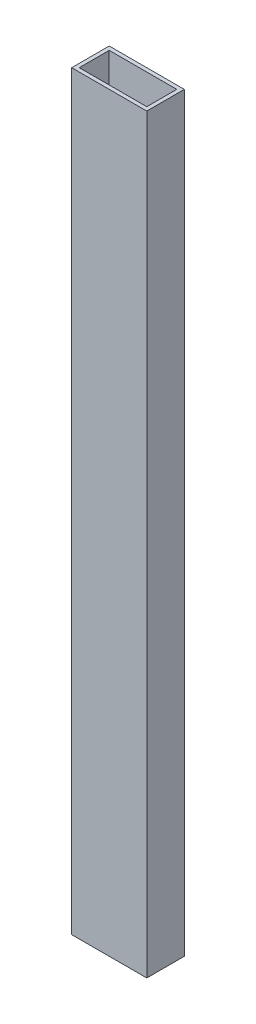
SolidWorks part; units mm, degrees
ref_plane "Plano frontal" through (0, 0, 0) normal (0, 0, 1) x (1, 0, 0)
ref_plane "Plano superior" through (0, 0, 0) normal (0, 1, 0) x (1, 0, 0)
ref_plane "Plano direito" through (0, 0, 0) normal (1, 0, 0) x (0, 0, -1)
sketch "Esboço1" plane through (0, 0, 0) normal (0, 1, 0) x (1, 0, 0)
  line L0 (-18, -8) -> (-18, 8)
  line L1 (-20, -10) -> (20, -10)
  line L2 (-20, -10) -> (-20, 10)
  line L3 (-20, 10) -> (20, 10)
  line L4 (20, -10) -> (20, 10)
  line L5 (-20, -10) -> (20, 10) construction
  line L6 (-20, 10) -> (20, -10) construction
  line L7 (-18, 8) -> (18, 8)
  line L8 (18, -8) -> (18, 8)
  line L9 (-18, -8) -> (18, -8)
  point P0 (0, 0)
  dimension "D1" = 40
  dimension "D2" = 20
  dimension "D3" = 2
sketch "Esboço2" plane through (0, 0, 0) normal (1, 0, 0) x (0, 0, -1)
  line L0 (0, 0) -> (0, -400)
  dimension "D1" = 400
sweep "Varredura1" add profiles "Esboço1" path "Esboço2"
equation "\"´40\"=20"
